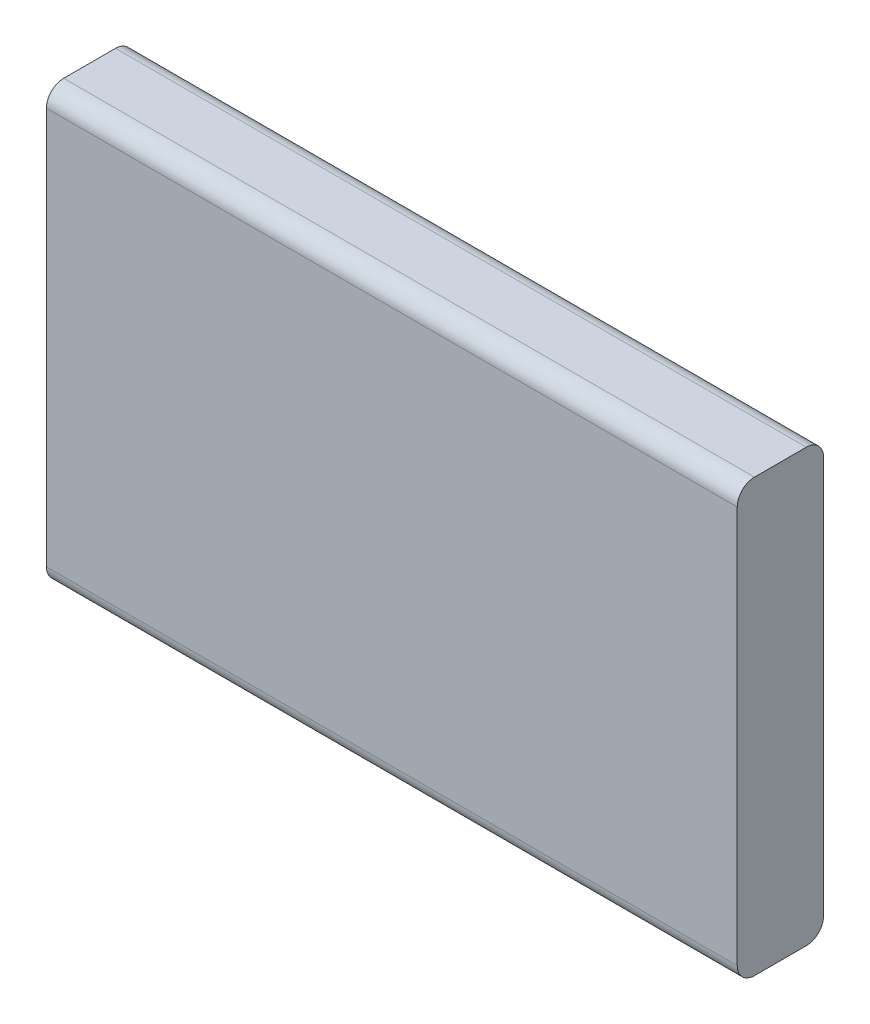
SolidWorks part; units mm, degrees
ref_plane "Front" through (0, 0, 0) normal (0, 0, 1) x (1, 0, 0)
ref_plane "Top" through (0, 0, 0) normal (0, 1, 0) x (1, 0, 0)
ref_plane "Right" through (0, 0, 0) normal (1, 0, 0) x (0, 0, -1)
sketch "草图1" plane through (0, 0, 0) normal (0, 0, 1) x (1, 0, 0)
  line L0 (0, 21.3541) -> (0, -26.2411) construction
  line L1 (-20, 12.5) -> (20, 12.5)
  line L2 (-20, 12.5) -> (-20, -12.5)
  line L3 (-20, -12.5) -> (20, -12.5)
  line L4 (20, 12.5) -> (20, -12.5)
  line L5 (-31.7302, 0) -> (31.6594, 0) construction
  dimension "D1" = 40
  dimension "D2" = 25
extrude "凸台-拉伸1" add sketch "草图1" against normal blind 5
ref_plane "基准面1" through (0, 0, 0) normal (0, 1, 0) x (1, 0, 0)
fillet "圆角2" radius 1 1 edges at (0, 12.5, 0)
fillet "圆角3" radius 1 3 edges at (0, 12.5, -5) (0, -12.5, 0) (0, -12.5, -5)
